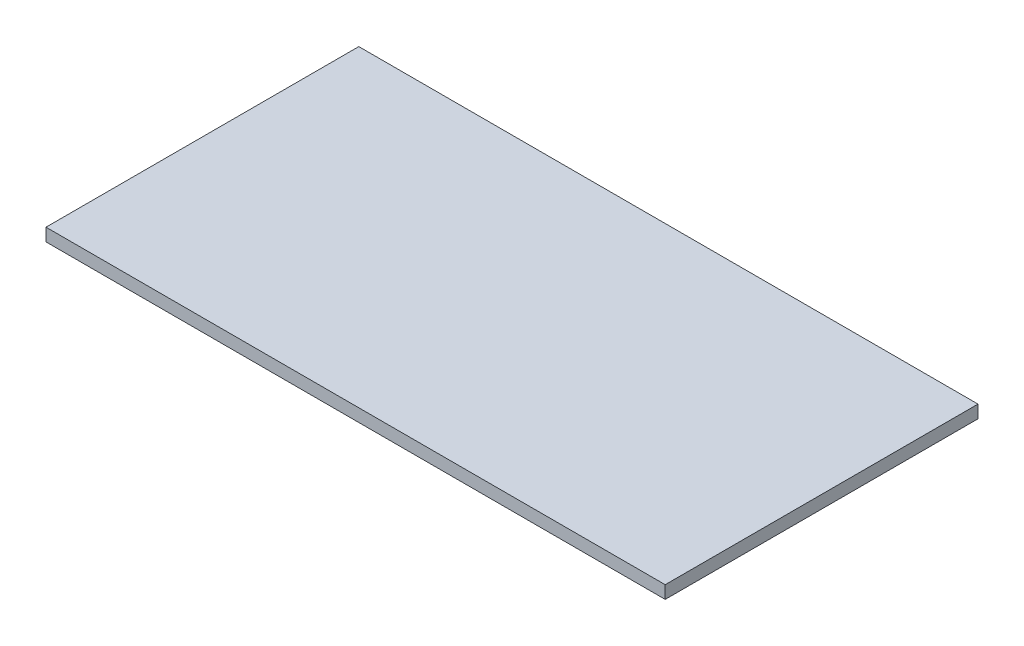
SolidWorks part; units mm, degrees
ref_plane "Front Plane" through (0, 0, 0) normal (0, 0, 1) x (1, 0, 0)
ref_plane "Top Plane" through (0, 0, 0) normal (0, 1, 0) x (1, 0, 0)
ref_plane "Right Plane" through (0, 0, 0) normal (1, 0, 0) x (0, 0, -1)
sketch "Sketch1" plane through (0, 0, 0) normal (0, 1, 0) x (1, 0, 0)
  line L1 (0, 0) -> (2463.8, 0)
  line L2 (0, 0) -> (0, 1244.6)
  line L3 (0, 1244.6) -> (2463.8, 1244.6)
  line L4 (2463.8, 0) -> (2463.8, 1244.6)
  dimension "D1" = 2463.8
  dimension "D2" = 1244.6
extrude "Boss-Extrude1" add sketch "Sketch1" along normal blind 50.8
